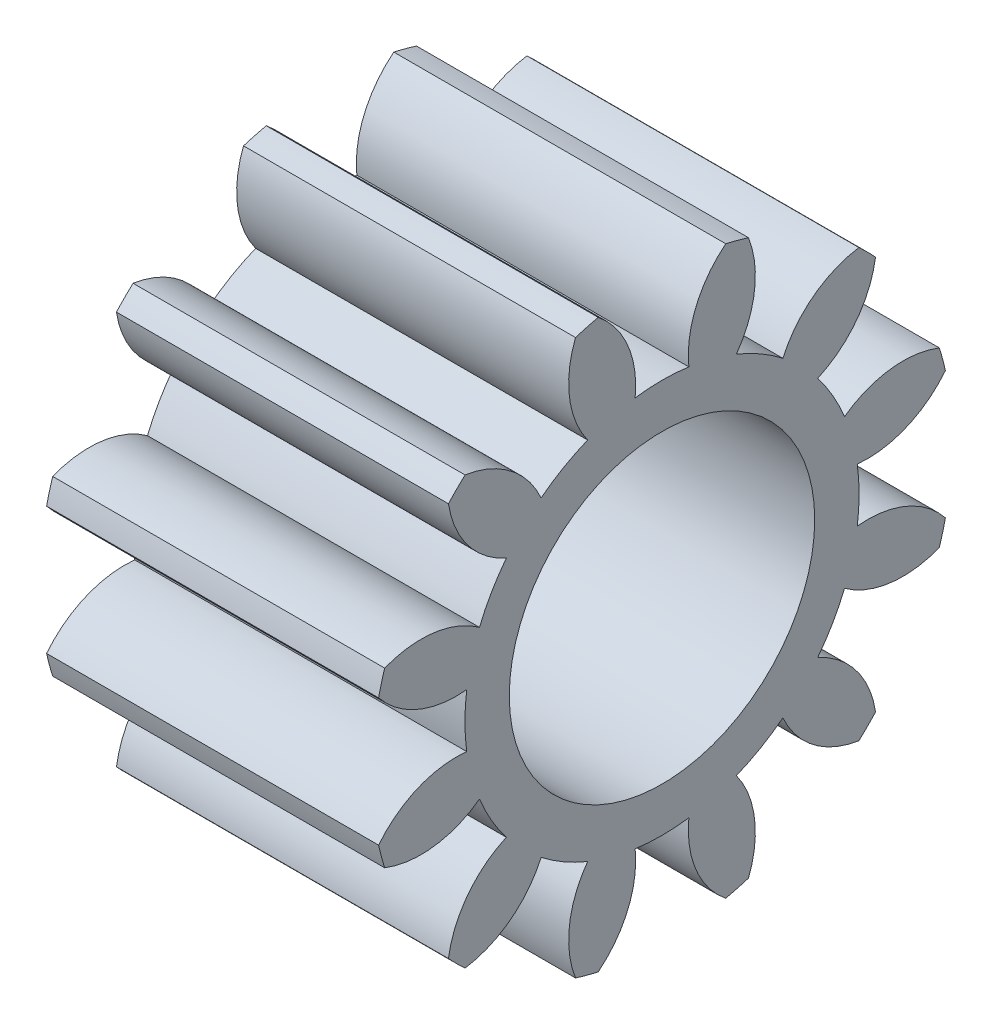
SolidWorks part; units mm, degrees
ref_plane "Plane1" through (0, 0, 0) normal (0, 0, 1) x (1, 0, 0)
ref_plane "Plane2" through (0, 0, 0) normal (0, 1, 0) x (1, 0, 0)
ref_plane "Plane3" through (0, 0, 0) normal (1, 0, 0) x (0, 0, -1)
sketch "HoldingSke" plane through (0, 0, 0) normal (0, 1, 0) x (1, 0, 0)
  line L0 (0, 0) -> (397.5192, -84.4953)
  line L1 (-15, 0) -> (100, 0) construction
  line L2 (0, 0) -> (-2.1039, 2.3779)
  line L3 (0, 0) -> (-11.863, 4.5341)
  line L4 (0, 0) -> (8.4473, 1.7955)
  line L5 (0, 0) -> (-47.5972, -17.7524)
  line L6 (0, 0) -> (-10.5278, -7.1032)
  line L7 (-2.1039, 2.3779) -> (8.8308, 51.9871)
  line L8 (-76.2, 54.61) -> (-69.596, 54.61)
  line L9 (-67.7845, 28.3722) -> (-49.3413, 33.142)
  line L10 (-76.2, 71.12) -> (104.1128, 71.12)
  line L11 (0, 0) -> (-12.7, 0)
  line L12 (-76.2, 101.6) -> (-76.1428, 101.6)
  line L13 (24.9733, 27.94) -> (52.9518, 28.4284)
  line L14 (24.9733, 27.94) -> (24.9746, 27.94)
  line L15 (24.9733, 27.94) -> (100.4006, 29.5858)
  circle A0 centre (0, 0) radius 3.175
  circle A1 centre (0, 0) radius 7.5394
  circle A2 centre (0, 0) radius 38.1
  circle A3 centre (0, 0) radius 3.175
  dimension "MHD" = 15.0787
  dimension "Hub_dia" = 76.2
  dimension "Bore" = 6.35
  dimension "MBD" = 6.35
  dimension "Num_teeth" = 12
  dimension "Pitch" = 406.4
  dimension "Overall_len" = 50.8
  dimension "Show_teeth" = 12
  dimension "Thickness" = 12.7
  dimension "OAL" = 50.8001
  dimension "T_dim" = 6.604
  dimension "Ap" = 14.5
  dimension "H" = 19.05
  dimension "Pitch_radius" = 180.3128
  dimension "Width" = 12.7
  dimension "Backlash" = 0.0571
  dimension "Addendum_fac" = 1
  dimension "Dedendum_fac" = 1.25
  dimension "Clearance_fac" = 0.25
  dimension "Dedendum_add" = 0.0013
sketch "BasProSke" plane through (0, 0, 0) normal (0, 1, 0) x (1, 0, 0)
  line L0 (-10, 0) -> (60, 0) construction
  line L1 (0, 0) -> (0, 11.1125)
  line L2 (0, 0) -> (12.7, 0)
  line L3 (12.7, 0) -> (12.7, 11.1125)
  line L4 (12.7, 11.1125) -> (0, 11.1125)
  dimension "Thickness" = 12.7
  dimension "Diameter" = 22.225
revolve "Base-Revolve" add sketch "BasProSke" angle 360 about L0
sketch "TooCutSke" plane through (0, 0, 0) normal (1, 0, 0) x (0, 0, -1)
  line L1 (0, 0) -> (0, 107) construction
  line L2 (0, 0) -> (-1.3431, 9.4298) construction
  line L3 (0, 0) -> (-4.8949, 18.2679) construction
  line L4 (-1.3431, 9.4298) -> (-2.4474, 9.1339) construction
  arc A0 (1.0269, 7.4691) -> (-1.0269, 7.4691) centre (0, 0) ccw
  arc A1 (2.4651, 10.8617) -> (-2.4651, 10.8617) centre (0, 0) ccw
  circle A2 centre (0, 0) radius 9.525 construction
  circle A3 centre (0, 0) radius 9.2216 construction
  arc A4 (-1.0269, 7.4691) -> (-2.4651, 10.8617) centre (-4.8164, 7.8638) ccw
  arc A5 (2.4651, 10.8617) -> (1.0269, 7.4691) centre (4.8164, 7.8638) ccw
  dimension "Root_dia" = 15.0787
  dimension "Overcut_dia" = 22.2758
  dimension "Pitch_dia" = 19.05
  dimension "Base_dia" = 18.4432
  dimension "Flank_rad" = 3.81
  dimension "Half_ang" = 15
  dimension "Half_CT" = 1.1432
extrude "ToothCut" cut sketch "TooCutSke" along normal through all
fillet "Breaks" [suppressed] radius 0.0318
fillet "RootFillets" [suppressed] radius 0.3981
pattern_circular "TeethCuts" count 12 every 30 about axis through (-10, 0, 0) along (1, 0, 0) of "ToothCut", "RootFillets", "Breaks"
sketch "HubNeaOneSke" plane through (0, 0, 0) normal (-1, 0, 0) x (0, 0, 1)
  circle A0 centre (0, 0) radius 7.5394
  dimension "Diameter" = 15.0787
extrude "HubNearOne" [suppressed] add sketch "HubNeaOneSke" along normal blind 38.1001
sketch "HubNeaBotSke" plane through (0, 0, 0) normal (-1, 0, 0) x (0, 0, 1)
  circle A0 centre (0, 0) radius 7.5394
  dimension "Diameter" = 15.0787
extrude "HubNearBoth" [suppressed] add sketch "HubNeaBotSke" along normal blind 19.05
ref_plane "FarPln" through (12.7, 0, 0) normal (1, 0, 0) x (0, 0, -1)
sketch "HubFarSke" plane through (12.7, 0, 0) normal (1, 0, 0) x (0, 0, -1)
  circle A0 centre (0, 0) radius 7.5394
  dimension "Diameter" = 15.0787
extrude "HubFar" [suppressed] add sketch "HubFarSke" along normal blind 19.05
sketch "BorSke" plane through (0, 0, 0) normal (1, 0, 0) x (0, 0, -1)
  circle A0 centre (0, 0) radius 3.175
  dimension "Diameter" = 6.35
extrude "Bore" cut sketch "BorSke" along normal mid plane 101.6001
sketch "KeySke" plane through (0, 0, 0) normal (1, 0, 0) x (0, 0, -1)
  line L0 (-0.127, 0) -> (-0.127, 3.429)
  line L1 (-0.127, 3.429) -> (0.127, 3.429)
  line L2 (0.127, 3.429) -> (0.127, 0)
  line L3 (0, 0) -> (0, 34) construction
  line L4 (-0.127, 0) -> (0.127, 0)
  dimension "Offset" = 3.429
  dimension "Width" = 0.254
extrude "Keyway" [suppressed] cut sketch "KeySke" along normal mid plane 101.6001
pattern_circular "Keyway2" [suppressed] count 2 every 90 about axis through (-10, 0, 0) along (1, 0, 0)
sketch "Sketch1" plane through (0, 0, 0) normal (1, 0, 0) x (0, 0, -1)
  circle A0 centre (0, 0) radius 9.525 construction
  dimension "D1" = 19.05
sketch "Sketch2" plane through (12.7, 0, 0) normal (1, 0, 0) x (0, 0, -1)
  circle A0 centre (0, 0) radius 5.842
  dimension "D1" = 11.684
extrude "Cut-Extrude1" cut sketch "Sketch2" against normal through all
equation "' \"Pitch@HoldingSke\" = 4"
equation "' \"Num_teeth@HoldingSke\" = 12"
equation "' \"Ap@HoldingSke\" =  20"
equation "' \"Ap@HoldingSke\" = 20"
equation "' \"Width@HoldingSke\" = 0.5"
equation "' \"Hub_dia@HoldingSke\"= 1"
equation "' \"Hub_dia@HoldingSke\" = 1"
equation "' \"Overall_len@HoldingSke\" = 1.0"
equation "' \"Bore@HoldingSke\" = 0.75"
equation "' \"T_dim@HoldingSke\" = 0.85"
equation "' \"Width@KeySke\" = 0.25"
equation "' \"Show_teeth@HoldingSke\" = 13"
equation "' \"Backlash@HoldingSke\" = 0.009"
equation "' \"Addendum_fac@HoldingSke\" = 1.0"
equation "' \"Dedendum_fac@HoldingSke\" = 1.25"
equation "' \"Dedendum_add@HoldingSke\" = 0.00005"
equation "' \"Clearance_fac@HoldingSke\" = 0.25"
equation "' \"Pitch@HoldingSke\" = 0.5"
equation "' \"Num_teeth@HoldingSke\" = 23"
equation "' \"Show_teeth@HoldingSke\" = 23"
equation "' \"Backlash@HoldingSke\" = 0.0375"
equation "\"Overcut_dia@TooCutSke\" = (\"Num_teeth@HoldingSke\" + 2 * \"Addendum_fac@HoldingSke\") / \"Pitch@HoldingSke\" + 0.002"
equation "\"Pitch_dia@TooCutSke\" = \"Num_teeth@HoldingSke\" / \"Pitch@HoldingSke\""
equation "\"Base_dia@TooCutSke\" = \"Num_teeth@HoldingSke\" / \"Pitch@HoldingSke\" * cos((\"Ap@HoldingSke\"  * 3.14159265 / 180))"
equation "\"Root_dia@TooCutSke\" = (\"Num_teeth@HoldingSke\" + 2) / \"Pitch@HoldingSke\" - 2 * (\"Addendum_fac@HoldingSke\" + \"Dedendum_fac@HoldingSke\") / \"Pitch@HoldingSke\" - \"Dedendum_add@HoldingSke\" * 2"
equation "\"Half_ang@TooCutSke\" = 180 / \"Num_teeth@HoldingSke\""
equation "\"Half_CT@TooCutSke\" = \"Num_teeth@HoldingSke\" / \"Pitch@HoldingSke\" * sin((3.14159265 / 2 / \"Num_teeth@HoldingSke\")) / 2 - 7 * \"Backlash@HoldingSke\" / 4"
equation "\"Flank_rad@TooCutSke\" = \"Num_teeth@HoldingSke\" / \"Pitch@HoldingSke\" / 5"
equation "\"Radius@RootFillets\" = \"Clearance_fac@HoldingSke\" / \"Pitch@HoldingSke\" + \"Dedendum_add@HoldingSke\""
equation "\"Break_rad@Breaks\" = 0.02 / \"Pitch@HoldingSke\""
equation "\"Thickness@HoldingSke\" = \"Width@HoldingSke\""
equation "\"OAL@HoldingSke\" = \"Thickness@HoldingSke\""
equation "\"MHD@HoldingSke\" = (\"Num_teeth@HoldingSke\" + 2) / \"Pitch@HoldingSke\" - 2 * (\"Addendum_fac@HoldingSke\" + \"Dedendum_fac@HoldingSke\")  / \"Pitch@HoldingSke\" - \"Dedendum_add@HoldingSke\" * 2"
equation "\"MBD@HoldingSke\" = (\"Num_teeth@HoldingSke\" + 2) / \"Pitch@HoldingSke\" - 2 * (\"Addendum_fac@HoldingSke\" + \"Dedendum_fac@HoldingSke\")  / \"Pitch@HoldingSke\" - \"Dedendum_add@HoldingSke\" * 2 - 0.002"
equation "\"MHD@HoldingSke\" = ((sgn( \"MHD@HoldingSke\" - \"Hub_dia@HoldingSke\" )-1)*( \"MHD@HoldingSke\" - \"Hub_dia@HoldingSke\" ))/-2+ \"Hub_dia@HoldingSke\""
equation "\"MBD@HoldingSke\" = ((sgn( \"MBD@HoldingSke\" - \"Bore@HoldingSke\" )-1)*( \"MBD@HoldingSke\" - \"Bore@HoldingSke\" ))/-2+ \"Bore@HoldingSke\""
equation "\"OAL@HoldingSke\" = ((sgn( \"OAL@HoldingSke\" - \"Overall_len@HoldingSke\" )+1)*( \"OAL@HoldingSke\" - \"Overall_len@HoldingSke\" ))/2 + \"Overall_len@HoldingSke\" + 0.000002"
equation "\"Num_teeth@TeethCuts\" = int( \"Show_teeth@HoldingSke\" ) + 1"
equation "\"Num_teeth@TeethCuts\" = ((sgn( \"Num_teeth@TeethCuts\" - \"Num_teeth@HoldingSke\" )-1)*( \"Num_teeth@TeethCuts\" - \"Num_teeth@HoldingSke\" ))/-2+ \"Num_teeth@HoldingSke\""
equation "\"Num_teeth@TeethCuts\" = ((sgn( \"Num_teeth@TeethCuts\" - 2.0)+1)*( \"Num_teeth@TeethCuts\" - 2.0))/2 +2.0"
equation "\"Angle@TeethCuts\" = 360.0 / \"Num_teeth@HoldingSke\""
equation "\"Diameter@BasProSke\" = (\"Num_teeth@HoldingSke\" + 2 * \"Addendum_fac@HoldingSke\") / \"Pitch@HoldingSke\""
equation "\"Thickness@BasProSke\"  = \"Thickness@HoldingSke\""
equation "' \"Fillet_rad@BasProSke\" =  \"Thickness@HoldingSke\" * 0.05"
equation "' \"Fillet_rad@BasProSke\" = \"Thickness@HoldingSke\" * 0.05"
equation "\"MHD@HoldingSke\" = ((sgn( \"MHD@HoldingSke\" - \"Root_dia@TooCutSke\" )-1)*( \"MHD@HoldingSke\" - \"Root_dia@TooCutSke\" ))/-2+ \"Root_dia@TooCutSke\""
equation "\"Diameter@HubNeaOneSke\" = \"MHD@HoldingSke\""
equation "\"Length@HubNearOne\" = \"OAL@HoldingSke\" - \"Thickness@BasProSke\""
equation "\"Diameter@HubNeaBotSke\" = \"MHD@HoldingSke\""
equation "\"Length@HubNearBoth\" = ( \"OAL@HoldingSke\" - \"Thickness@BasProSke\" ) / 2.0"
equation "\"Thickness@FarPln\" = \"Thickness@BasProSke\""
equation "\"Diameter@HubFarSke\" = \"MHD@HoldingSke\""
equation "\"Length@HubFar\" = ( \"OAL@HoldingSke\" - \"Thickness@BasProSke\" ) / 2.0"
equation "\"Diameter@BorSke\" = \"MBD@HoldingSke\""
equation "\"D1@Bore\" = \"OAL@HoldingSke\" * 2.0"
equation "\"D1@Keyway\" = \"OAL@HoldingSke\" * 2.0"
equation "\"Offset@KeySke\" = \"T_dim@HoldingSke\" - \"MBD@HoldingSke\" / 2.0"
